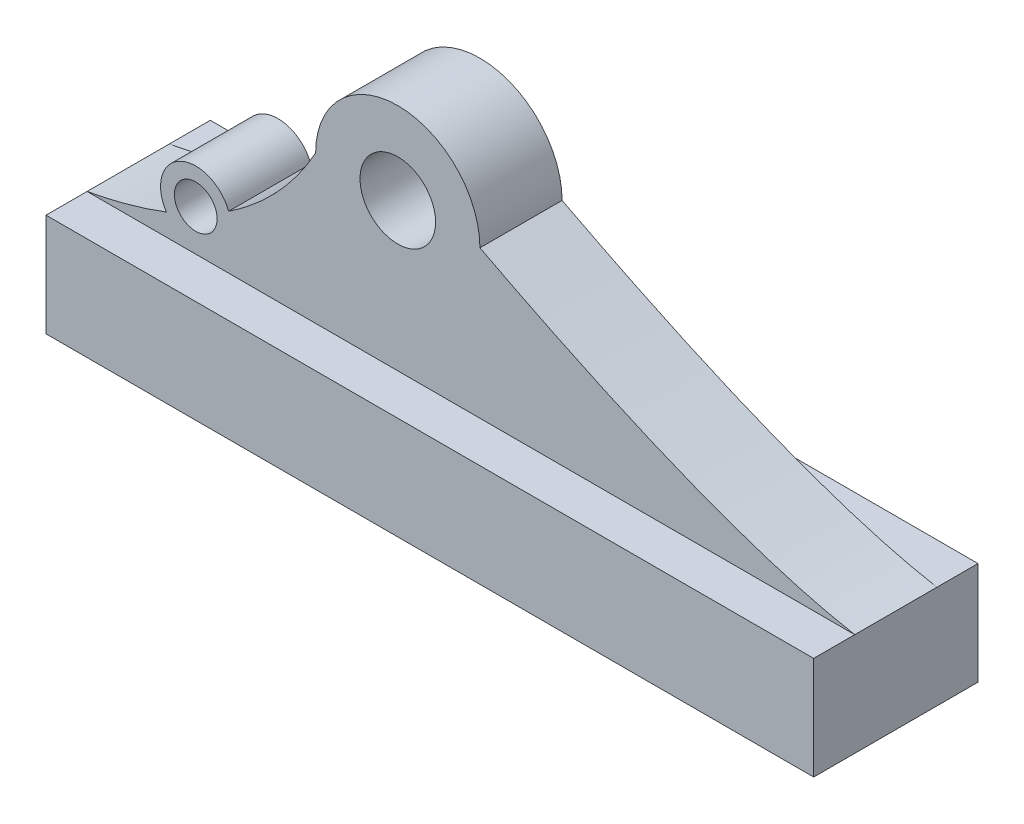
SolidWorks part; units mm, degrees
ref_plane "Front Plane" through (0, 0, 0) normal (0, 0, 1) x (1, 0, 0)
ref_plane "Top Plane" through (0, 0, 0) normal (0, 1, 0) x (1, 0, 0)
ref_plane "Right Plane" through (0, 0, 0) normal (1, 0, 0) x (0, 0, -1)
sketch "Sketch1" plane through (0, 0, 0) normal (0, 0, 1) x (1, 0, 0)
  line L0 (-10.268, 0) -> (13.0927, 0)
  line L1 (13.0927, 0) -> (13.0927, 3.1275)
  line L2 (-10.268, 0) -> (-10.268, 3.1275)
  circle A0 centre (-0.8135, 7.6184) radius 1.15 construction
  circle A1 centre (-0.8135, 7.6184) radius 1.15
  arc A2 (1.6865, 7.6184) -> (-3.3135, 7.6184) centre (-0.8135, 7.6184) ccw
  arc A3 (-3.0183, 8.7969) -> (1.6865, 7.6184) centre (-0.8135, 7.6184) ccw construction
  spline S0 degree 2 poles (-10.268, 3.1275) (-5.3063, 4.0306) (-3.3135, 7.6184) knots 0 0 0 1 1 1
  spline S1 degree 2 poles (1.6865, 7.6184) (8.886, 3.8754) (13.0927, 3.1275) knots 0 0 0 1 1 1
extrude "Boss-Extrude1" add sketch "Sketch1" along normal mid plane 2.5
sketch "Sketch2" plane through (0, 0, 0) normal (0, 0, 1) x (1, 0, 0)
  line L1 (-10.268, 3.1275) -> (13.0927, 3.1275)
  line L2 (-10.268, 3.1275) -> (-10.268, 0)
  line L3 (-10.268, 0) -> (13.0927, 0)
  line L4 (13.0927, 3.1275) -> (13.0927, 0)
  line L5 (-10.268, 3.1275) -> (13.0927, 0) construction
  line L6 (-10.268, 0) -> (13.0927, 3.1275) construction
  point P4 (1.4123, 1.5638)
extrude "Boss-Extrude2" add sketch "Sketch2" along normal mid plane 5
sketch "Sketch3" plane through (0, 0, -1.25) normal (0, 0, -1) x (-1, 0, 0)
  circle A0 centre (6.9617, 4.381) radius 1.0708
extrude "Boss-Extrude3" add sketch "Sketch3" against normal up to surface (2.5 mm away) up to face at (0.3365, 7.6184, 1.25)
sketch "Sketch4" plane through (0, 0, -1.25) normal (0, 0, -1) x (-1, 0, 0)
  circle A0 centre (6.9617, 4.381) radius 0.65
  dimension "D1" = 1.3
extrude "Cut-Extrude1" cut sketch "Sketch4" against normal through all both and the other way through all
move or copy body "Body-Move/Copy1" bodies to move or copy 104 copy no translate (0.81, -7.62, 0)
